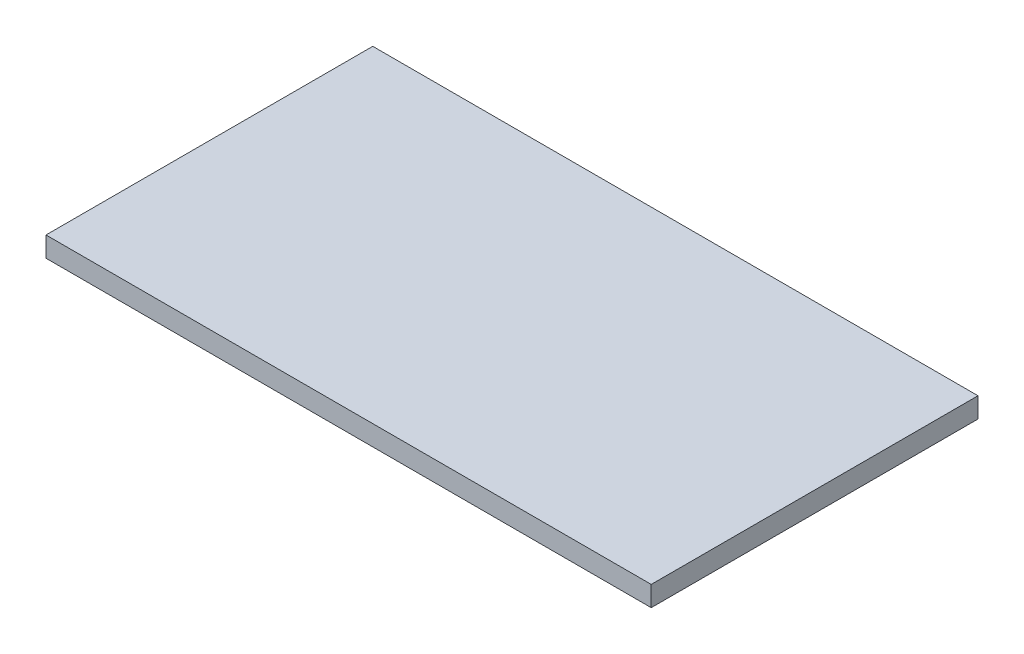
SolidWorks part; units mm, degrees
ref_plane "Спереди" through (0, 0, 0) normal (0, 0, 1) x (1, 0, 0)
ref_plane "Сверху" through (0, 0, 0) normal (0, 1, 0) x (1, 0, 0)
ref_plane "Справа" through (0, 0, 0) normal (1, 0, 0) x (0, 0, -1)
sketch "Эскиз1" plane through (0, 0, 0) normal (0, 1, 0) x (1, 0, 0)
  line L0 (150, 209.5481) -> (150, -36.4371) construction
  line L1 (0, 49.5481) -> (150, 49.5481)
  line L2 (0, 49.5481) -> (0, -31.4371)
  line L3 (0, -31.4371) -> (150, -31.4371)
  line L4 (150, 49.5481) -> (150, -31.4371)
extrude "Вытянуть1" add sketch "Эскиз1" along normal blind 5
